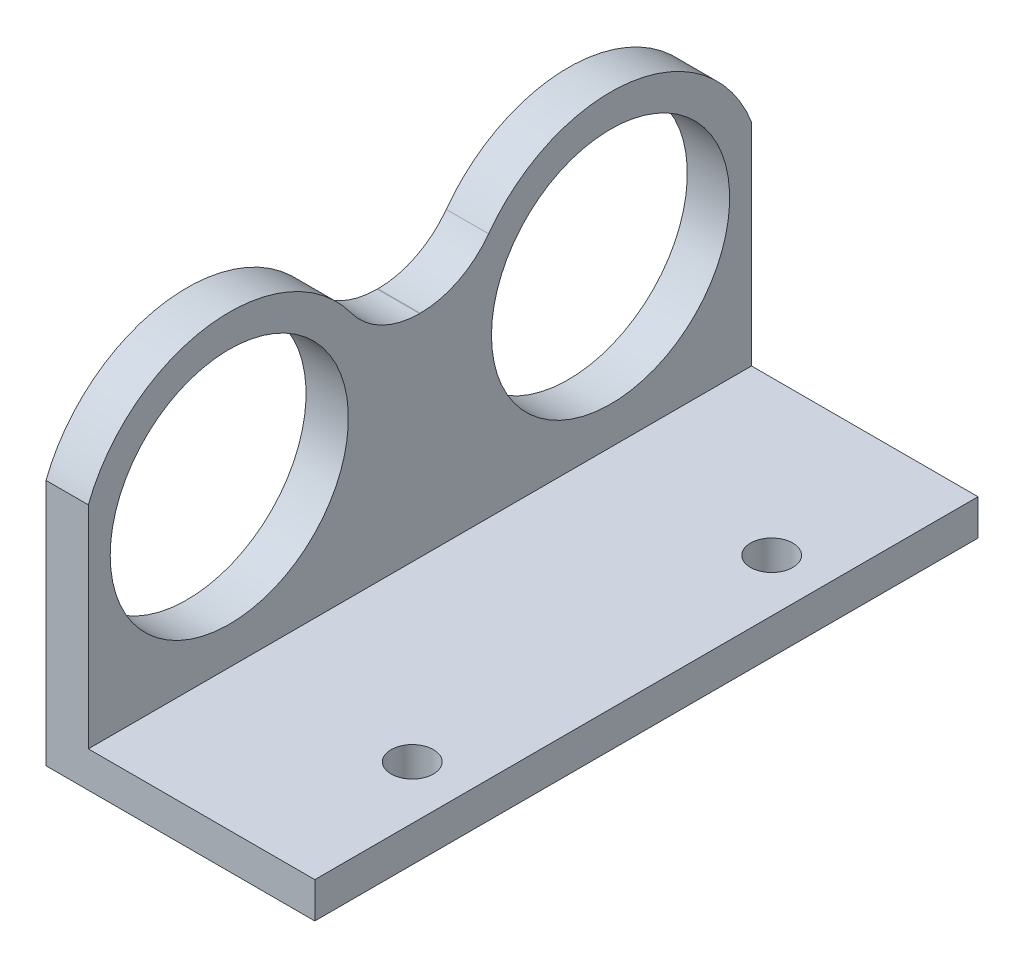
SolidWorks part; units mm, degrees
ref_plane "Front Plane" through (0, 0, 0) normal (0, 0, 1) x (1, 0, 0)
ref_plane "Top Plane" through (0, 0, 0) normal (0, 1, 0) x (1, 0, 0)
ref_plane "Right Plane" through (0, 0, 0) normal (1, 0, 0) x (0, 0, -1)
sketch "Sketch1" plane through (0, 0, 0) normal (0, 1, 0) x (1, 0, 0)
  line L1 (0, 0) -> (19.05, 0)
  line L2 (0, 0) -> (0, 47)
  line L3 (0, 47) -> (19.05, 47)
  line L4 (19.05, 0) -> (19.05, 47)
  dimension "D1" = 19.05
  dimension "D2" = 47
extrude "Boss-Extrude1" add sketch "Sketch1" along normal blind 2.54
sketch "Sketch2" plane through (0, 0, 0) normal (-1, 0, 0) x (0, 0, 1)
  line L0 (-37.01, 5.19) -> (-28.5148, 5.19) construction
  line L1 (-47, 2.54) -> (0, 2.54)
  line L2 (-47, 2.54) -> (-47, 17.5165)
  line L4 (0, 2.54) -> (0, 17.5165)
  line L5 (-17.4819, 17.5165) -> (-2.4981, 17.5165)
  line L6 (-23.5, 0) -> (-23.5, 25.3448) construction
  line L7 (-47, 0) -> (0, 0) construction
  line L8 (-23.5269, 17.5165) -> (-23.4731, 17.5165)
  line L9 (-45.45, 20.2384) -> (-45.45, 21.1304) construction
  circle A0 centre (-37.01, 13.63) radius 8.44
  arc A2 (-28.3655, 19.9686) -> (-47, 17.5165) centre (-37.01, 13.63) ccw
  circle A3 centre (-9.99, 13.63) radius 8.44
  arc A4 (-18.6345, 19.9686) -> (0, 17.5165) centre (-9.99, 13.63) cw
  arc A5 (-18.6345, 19.9686) -> (-23.4731, 17.5165) centre (-23.4731, 23.5165) cw
  arc A6 (-23.5269, 17.5165) -> (-28.3655, 19.9686) centre (-23.5269, 23.5165) cw
  point P23 (-19.98, 17.5165)
  point P26 (-27.02, 17.5165)
  line M15 (0, 2.54) -> (-47, 2.54)
  dimension "D2" = 16.88
  dimension "D3" = 6
  dimension "D1" = 2.65
extrude "Boss-Extrude2" add sketch "Sketch2" against normal blind 3 contours L8 A6 A2 L2 L4 A4 A5 A3 A0 M15
sketch "Sketch3" plane through (0, 2.54, 0) normal (0, 1, 0) x (1, 0, 0)
  line L0 (15.2745, 9.1839) -> (10.2209, 9.1839) construction
  line L1 (16.7745, 10.6839) -> (16.7745, 13.9637) construction
  line L3 (19.05, 0) -> (19.05, 47) construction
  line L4 (19.05, 23.5) -> (-5.5696, 23.5) construction
  circle A0 centre (15.2745, 10.6839) radius 1.5
  circle A3 centre (15.33, 36.096) radius 1.5
  dimension "D1" = 3
  dimension "D2" = 3
extrude "Cut-Extrude1" cut sketch "Sketch3" against normal through all
